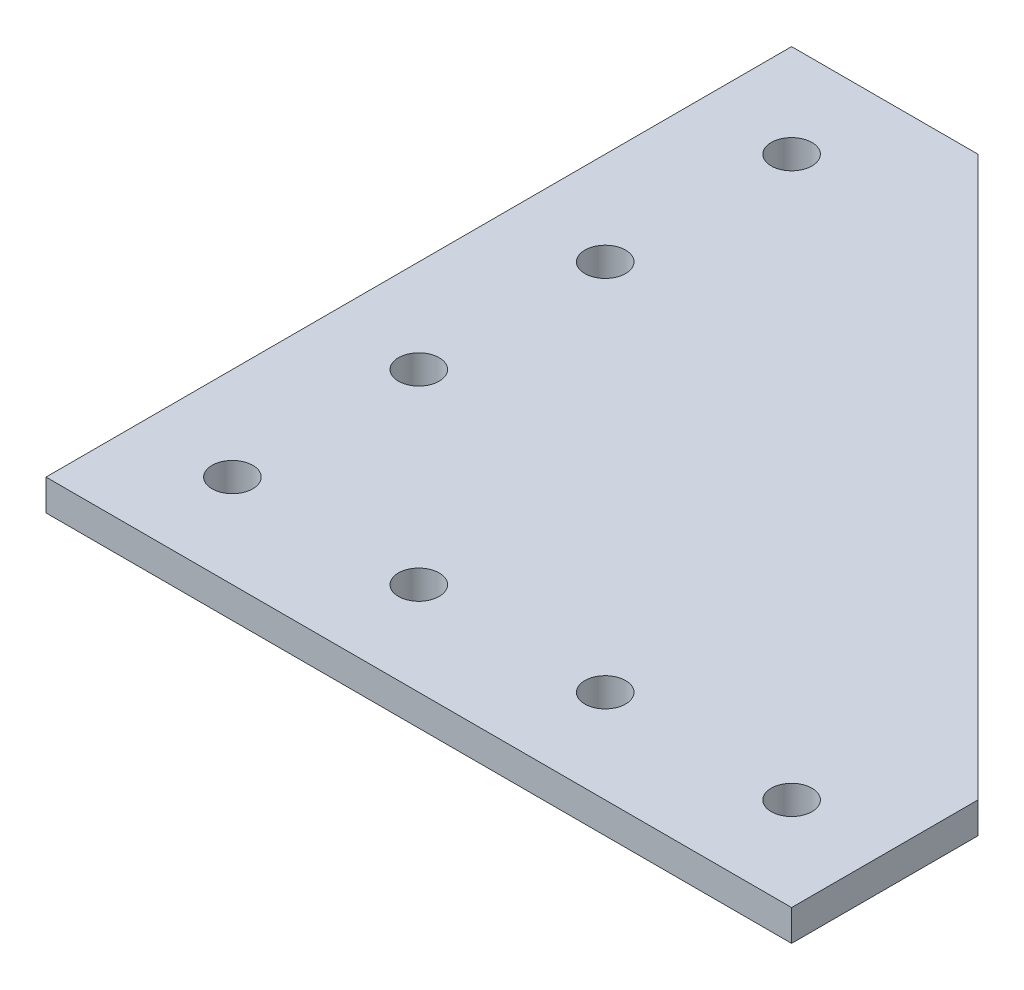
SolidWorks part; units mm, degrees
ref_plane "Front Plane" through (0, 0, 0) normal (0, 0, 1) x (1, 0, 0)
ref_plane "Top Plane" through (0, 0, 0) normal (0, 1, 0) x (1, 0, 0)
ref_plane "Right Plane" through (0, 0, 0) normal (1, 0, 0) x (0, 0, -1)
sketch "Sketch1" plane through (0, 0, 0) normal (0, 1, 0) x (1, 0, 0)
  line L0 (-103.3021, 104.8732) -> (-103.3021, -47.5268)
  line L1 (-103.3021, -47.5268) -> (49.0979, -47.5268)
  line L2 (49.0979, -47.5268) -> (49.0979, -9.4268)
  line L3 (49.0979, -9.4268) -> (-65.2021, 104.8732)
  line L4 (-65.2021, 104.8732) -> (-103.3021, 104.8732)
  circle A0 centre (-84.2521, 85.8232) radius 4.1656
  circle A1 centre (-84.2521, 47.7232) radius 4.1656
  circle A2 centre (-84.2521, 9.6232) radius 4.1656
  circle A3 centre (-84.2521, -28.4768) radius 4.1656
  circle A4 centre (-46.1521, -28.4768) radius 4.1656
  circle A5 centre (-8.0521, -28.4768) radius 4.1656
  circle A6 centre (30.0479, -28.4768) radius 4.1656
  dimension "D5" = 19.05
  dimension "D1" = 38.1
  dimension "D2" = 38.1
  dimension "D3" = 152.4
  dimension "D4" = 152.4
  dimension "D6" = 19.05
  dimension "D7" = 4
  dimension "D8" = 4
extrude "Boss-Extrude2" add sketch "Sketch1" along normal blind 6.35
